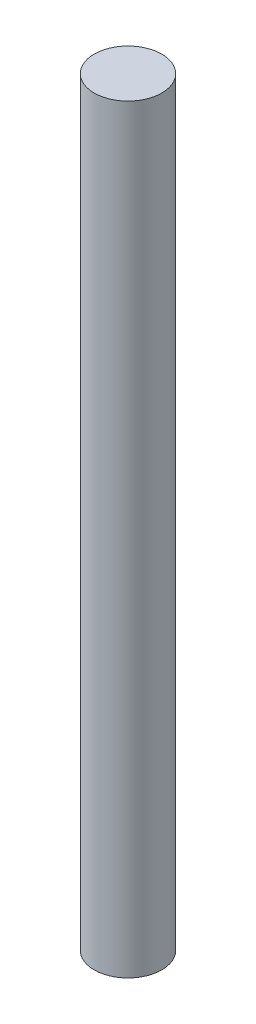
SolidWorks part; units mm, degrees
ref_plane "前视基准面" through (0, 0, 0) normal (0, 0, 1) x (1, 0, 0)
ref_plane "上视基准面" through (0, 0, 0) normal (0, 1, 0) x (1, 0, 0)
ref_plane "右视基准面" through (0, 0, 0) normal (1, 0, 0) x (0, 0, -1)
sketch "草图1" plane through (0, 0, 0) normal (0, 1, 0) x (1, 0, 0)
  circle A0 centre (0, 0) radius 40
  dimension "D1" = 80
extrude "凸台-拉伸1" add sketch "草图1" along normal mid plane 900
